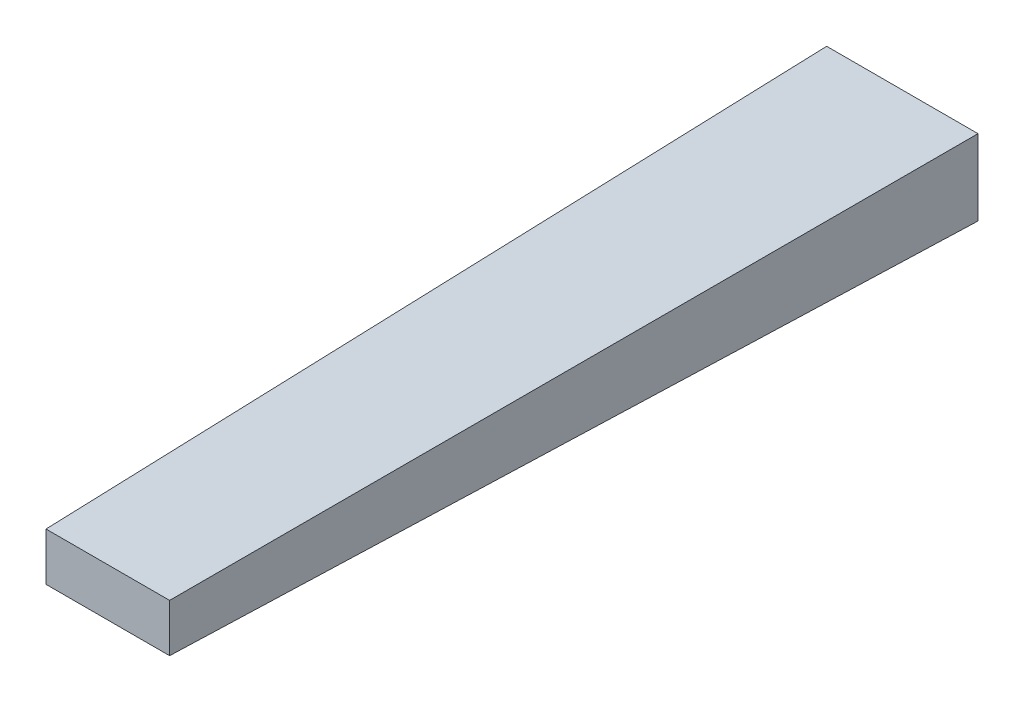
SolidWorks part; units mm, degrees
material "1060 Alloy"
ref_plane "Front Plane" through (0, 0, 0) normal (0, 0, 1) x (1, 0, 0)
ref_plane "Top Plane" through (0, 0, 0) normal (0, 1, 0) x (1, 0, 0)
ref_plane "Right Plane" through (0, 0, 0) normal (1, 0, 0) x (0, 0, -1)
sketch "Sketch2" plane through (0, 0, 0) normal (0, 0, 1) x (1, 0, 0)
  line L1 (-100, 50) -> (100, 50)
  line L2 (-100, 50) -> (-100, -50)
  line L3 (-100, -50) -> (100, -50)
  line L4 (100, 50) -> (100, -50)
  line L5 (-100, 50) -> (100, -50) construction
  line L6 (-100, -50) -> (100, 50) construction
  point P0 (0, 0)
  dimension "D1" = 100
  dimension "D2" = 200
extrude "Boss-Extrude1" add sketch "Sketch2" along normal blind 1050 draft 1
